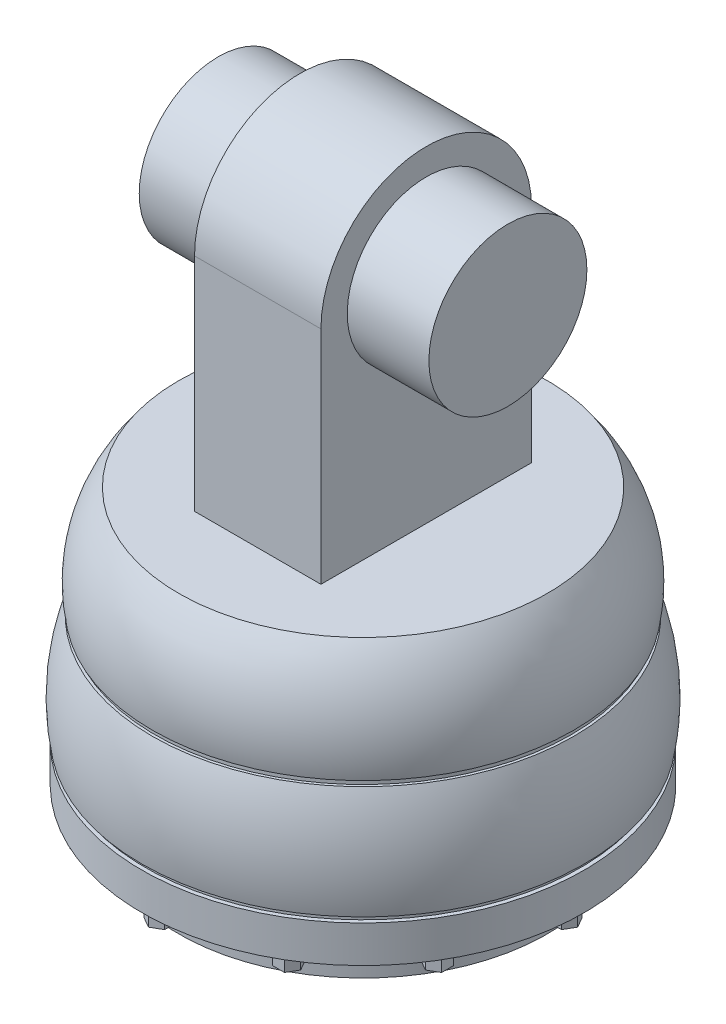
SolidWorks part; units mm, degrees
ref_plane "Front Plane" through (0, 0, 0) normal (0, 0, 1) x (1, 0, 0)
ref_plane "Top Plane" through (0, 0, 0) normal (0, 1, 0) x (1, 0, 0)
ref_plane "Right Plane" through (0, 0, 0) normal (1, 0, 0) x (0, 0, -1)
sketch "Sketch1" plane through (0, 0, 0) normal (0, 0, 1) x (1, 0, 0)
  line L0 (0, 0) -> (-35, 0)
  line L1 (0, 0) -> (0, -20)
  line L2 (0, -20) -> (-40, -20)
  arc A0 (-35, 0) -> (-40, -20) centre (-15.404, -15.524) ccw
  dimension "D4" = 25
  dimension "D1" = 35
  dimension "D2" = 20
  dimension "D3" = 40
revolve "Revolve1" add sketch "Sketch1" angle 360 about L1
sketch "Sketch2" plane through (0, -20, 0) normal (0, -1, 0) x (1, 0, 0)
  circle A0 centre (0, 0) radius 39.5
  dimension "D1" = 79
extrude "Boss-Extrude1" add sketch "Sketch2" along normal blind 1
sketch "Sketch3" plane through (0, 0, 0) normal (1, 0, 0) x (0, 0, -1)
  line L0 (0, -21) -> (-40, -21)
  line L1 (-39.5, -21) -> (39.5, -21) construction
  line L2 (0, -21) -> (0, -41)
  line L3 (0, -41) -> (-42, -41)
  arc A0 (-42, -41) -> (-40, -21) centre (-5.5677, -34.5432) cw
  dimension "D4" = 37
  dimension "D1" = 40
  dimension "D2" = 20
  dimension "D3" = 42
revolve "Revolve2" add sketch "Sketch3" angle 360 about L2
sketch "Sketch4" plane through (0, -41, 0) normal (0, -1, 0) x (1, 0, 0)
  circle A0 centre (0, 0) radius 41.25
  dimension "D1" = 82.5
extrude "Boss-Extrude2" add sketch "Sketch4" along normal blind 1
sketch "Sketch5" plane through (0, -42, 0) normal (0, -1, 0) x (1, 0, 0)
  circle A0 centre (0, 0) radius 42
  dimension "D1" = 84
extrude "Boss-Extrude3" add sketch "Sketch5" along normal blind 7
sketch "Sketch6" plane through (0, -49, 0) normal (0, -1, 0) x (1, 0, 0)
  circle A0 centre (0, 0) radius 35
  dimension "D1" = 70
extrude "Boss-Extrude4" add sketch "Sketch6" along normal blind 7
sketch "Sketch7" plane through (0, -49, 0) normal (0, -1, 0) x (1, 0, 0)
  line L0 (40.75, 0) -> (40.4486, 0)
  line L1 (39.0476, 0.9486) -> (37.9524, 0.9486)
  line L2 (40.75, 0) -> (39.625, 1.9486)
  line L3 (39.625, 1.9486) -> (37.375, 1.9486)
  line L4 (37.375, 1.9486) -> (36.25, 0)
  line L5 (36.25, 0) -> (37.375, -1.9486)
  line L6 (37.375, -1.9486) -> (39.625, -1.9486)
  line L7 (39.625, -1.9486) -> (40.75, 0)
  line L8 (37.9524, 0.9486) -> (37.4047, 0)
  line L9 (37.4047, 0) -> (37.9524, -0.9486)
  line L10 (37.9524, -0.9486) -> (39.0476, -0.9486)
  line L11 (39.0476, -0.9486) -> (39.5953, 0)
  line L12 (39.5953, 0) -> (39.0476, 0.9486)
  line L13 (36.5514, 0) -> (36.25, 0)
  circle A3 centre (38.5, 0) radius 1.9486 construction
  dimension "D1" = 4.5
  dimension "D2" = 1
extrude "Boss-Extrude7" add sketch "Sketch7" along normal blind 3
pattern_circular "CirPattern2" count 12 over 360 about axis through (0, 0, 0) along (0, 1, 0) of "Boss-Extrude7"
sketch "Sketch8" plane through (0, -56, 0) normal (0, -1, 0) x (1, 0, 0)
  circle A0 centre (0, 0) radius 15
  dimension "D1" = 30
extrude "Boss-Extrude8" add sketch "Sketch8" along normal blind 10
sketch "Sketch9" plane through (0, 0, 0) normal (0, 1, 0) x (1, 0, 0)
  line L1 (-12, -20) -> (12, -20)
  line L2 (-12, -20) -> (-12, 20)
  line L3 (-12, 20) -> (12, 20)
  line L4 (12, -20) -> (12, 20)
  line L5 (-12, -20) -> (12, 20) construction
  line L6 (-12, 20) -> (12, -20) construction
  point P0 (0, 0)
  dimension "D1" = 24
  dimension "D2" = 40
extrude "Boss-Extrude9" add sketch "Sketch9" along normal blind 42
sketch "Sketch10" plane through (-12, 0, 0) normal (-1, 0, 0) x (0, 0, 1)
  line L0 (-20, 42) -> (20, 42) construction
  line L1 (-20, 42) -> (20, 42)
  arc A0 (20, 42) -> (-20, 42) centre (0, 42) ccw
extrude "Boss-Extrude10" add sketch "Sketch10" against normal up to vertex
sketch "Sketch11" plane through (-12, 0, 0) normal (-1, 0, 0) x (0, 0, 1)
  circle A0 centre (0, 42) radius 15
  dimension "D1" = 30
extrude "Boss-Extrude11" add sketch "Sketch11" along normal blind 15.5
sketch "Sketch12" plane through (12, 0, 0) normal (1, 0, 0) x (0, 0, -1)
  circle A0 centre (0, 42) radius 15
  dimension "D1" = 30
extrude "Boss-Extrude12" add sketch "Sketch12" along normal blind 15.5
